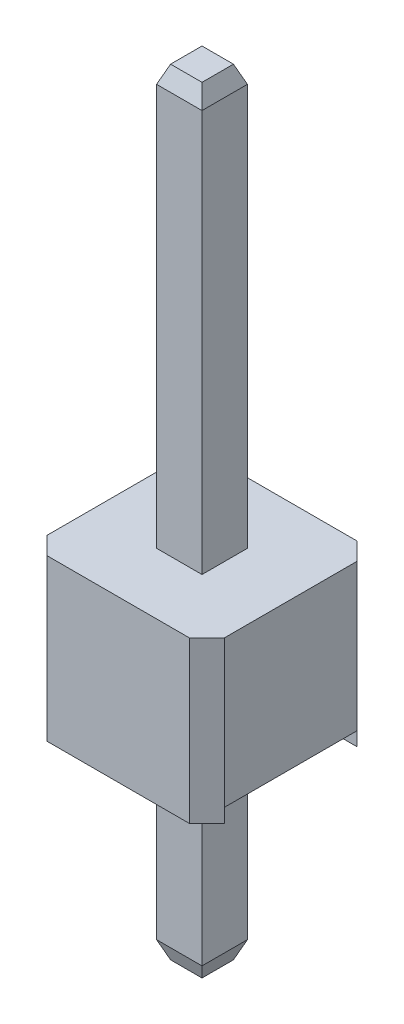
SolidWorks part; units mm, degrees
ref_plane "Front Plane" through (0, 0, 0) normal (0, 0, 1) x (1, 0, 0)
ref_plane "Top Plane" through (0, 0, 0) normal (0, 1, 0) x (1, 0, 0)
ref_plane "Right Plane" through (0, 0, 0) normal (1, 0, 0) x (0, 0, -1)
sketch "Sketch1" plane through (0, 0, 0) normal (0, 1, 0) x (1, 0, 0)
  line L1 (0, 0) -> (0.65, 0)
  line L2 (0, 0) -> (0, -0.65)
  line L3 (0, -0.65) -> (0.65, -0.65)
  line L4 (0.65, 0) -> (0.65, -0.65)
  dimension "D1" = 0.65
  dimension "D2" = 0.65
extrude "Boss-Extrude1" add sketch "Sketch1" along normal blind 11.3
chamfer "Chamfer1" distance 0.25 distance2 0.1 4 edges at (0.325, 11.3, 0) (0.65, 11.3, 0.325) (0.325, 11.3, 0.65) (0, 11.3, 0.325)
chamfer "Chamfer2" distance 0.1 distance2 0.25 4 edges at (0.325, 0, 0.65) (0.65, 0, 0.325) (0.325, 0, 0) (0, 0, 0.325)
ref_plane "Plane1" through (0, 3, 0) normal (0, -1, 0) x (-1, 0, 0)
sketch "Sketch2" plane through (0, 3, 0) normal (0, -1, 0) x (-1, 0, 0)
  line L0 (-0.65, -0.325) -> (0, -0.325) construction
  line L5 (-1.595, 0.875) -> (0.945, 0.875)
  line L6 (-1.595, 0.875) -> (-1.595, -1.525)
  line L7 (-1.595, -1.525) -> (0.945, -1.525)
  line L8 (0.945, 0.875) -> (0.945, -1.525)
  line L9 (-0.65, -0.65) -> (-0.65, 0) construction
  line L10 (0, 0) -> (0, -0.65) construction
  line L11 (-0.325, -0.325) -> (-2.865, -0.325) construction
  point P10 (-1.595, -0.325)
  dimension "D1" = 2.4
  dimension "D2" = 1.2
  dimension "D3" = 2.54
  dimension "D4" = 1.27
extrude "Boss-Extrude2" add sketch "Sketch2" against normal blind 2.3
chamfer "Chamfer3" distance 0.25 angle 45 4 edges at (-0.945, 4.15, -0.875) (-0.945, 4.15, 1.525) (1.595, 4.15, 1.525) (1.595, 4.15, -0.875)
sketch "Sketch6" plane through (1.595, 0, 0) normal (1, 0, 0) x (0, 0, -1)
  line L0 (-1.527, 3) -> (1.527, 3) construction
  line L1 (-1.275, 3) -> (0.625, 3)
  line L2 (-1.275, 3) -> (-1.275, 3.2)
  line L3 (-1.275, 3.2) -> (0.625, 3.2)
  line L4 (0.625, 3) -> (0.625, 3.2)
  line L5 (-1.275, 5.3) -> (-1.275, 3) construction
  line L6 (0.625, 3) -> (0.625, 5.3) construction
  dimension "D1" = 0.2
extrude "Cut-Extrude5" cut sketch "Sketch6" against normal blind 6
sketch "Sketch7" plane through (0, 3.2, 0) normal (0, -1, 0) x (1, 0, 0)
  line L1 (0, 0) -> (0.65, 0)
  line L2 (0, 0) -> (0, 0.65)
  line L3 (0, 0.65) -> (0.65, 0.65)
  line L4 (0.65, 0) -> (0.65, 0.65)
extrude "Boss-Extrude4" add sketch "Sketch7" along normal blind 3
chamfer "Chamfer5" distance 0.25 distance2 0.1 4 edges at (0.325, 0.2, 0.65) (0.65, 0.2, 0.325) (0.325, 0.2, 0) (0, 0.2, 0.325)
